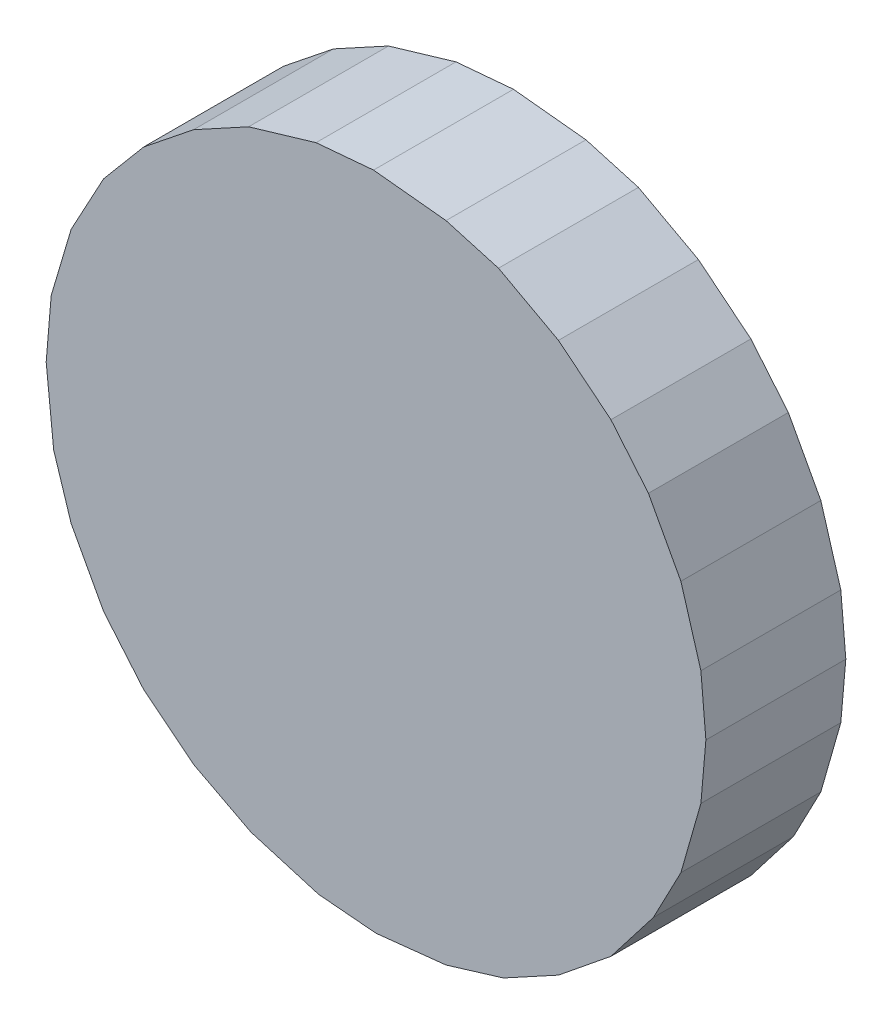
SolidWorks part; units mm, degrees
ref_plane "前视基准面" through (0, 0, 0) normal (0, 0, 1) x (1, 0, 0)
ref_plane "上视基准面" through (0, 0, 0) normal (0, 1, 0) x (1, 0, 0)
ref_plane "右视基准面" through (0, 0, 0) normal (1, 0, 0) x (0, 0, -1)
sketch "草图1" plane through (0, 0, 0) normal (0, 0, 1) x (1, 0, 0)
  line L0 (0, -6.6) -> (1.4, -6.45)
  line L1 (1.4, -6.45) -> (2.55, -6.1)
  line L2 (2.55, -6.1) -> (3.65, -5.5)
  line L3 (3.65, -5.5) -> (4.7, -4.65)
  line L4 (4.7, -4.65) -> (5.55, -3.55)
  line L5 (5.55, -3.55) -> (6.1, -2.5)
  line L6 (6.1, -2.5) -> (6.5, -1.1)
  line L7 (6.5, -1.1) -> (6.6, 0.05)
  line L8 (6.6, 0.05) -> (6.5, 1.2)
  line L9 (6.5, 1.2) -> (6.1, 2.55)
  line L10 (6.1, 2.55) -> (5.45, 3.75)
  line L11 (5.45, 3.75) -> (4.7, 4.65)
  line L12 (4.7, 4.65) -> (3.65, 5.5)
  line L13 (3.65, 5.5) -> (2.45, 6.15)
  line L14 (2.45, 6.15) -> (1.4, 6.45)
  line L15 (1.4, 6.45) -> (-0.05, 6.6)
  line L16 (-0.05, 6.6) -> (-1.2, 6.5)
  line L17 (-1.2, 6.5) -> (-2.55, 6.1)
  line L18 (-2.55, 6.1) -> (-3.65, 5.5)
  line L19 (-3.65, 5.5) -> (-4.65, 4.7)
  line L20 (-4.65, 4.7) -> (-5.45, 3.75)
  line L21 (-5.45, 3.75) -> (-6.1, 2.55)
  line L22 (-6.1, 2.55) -> (-6.5, 1.2)
  line L23 (-6.5, 1.2) -> (-6.6, 0)
  line L24 (-6.6, 0) -> (-6.45, -1.45)
  line L25 (-6.45, -1.45) -> (-6.1, -2.55)
  line L26 (-6.1, -2.55) -> (-5.45, -3.75)
  line L27 (-5.45, -3.75) -> (-4.65, -4.7)
  line L28 (-4.65, -4.7) -> (-3.65, -5.5)
  line L29 (-3.65, -5.5) -> (-2.5, -6.1)
  line L30 (-2.5, -6.1) -> (-1.15, -6.5)
  line L31 (-1.15, -6.5) -> (0, -6.6)
extrude "Component_Outline" add sketch "草图1" along normal blind 2.8 separate body
sketch3d "3D草图1"
  line L0 (0, 0, 0) -> (1, 0, 0)
  line L1 (0, 0, 0) -> (0, 1, 0)
  line L2 (0, 0, 0) -> (0, 0, 1)
  point P0 (0, 0, 0)
